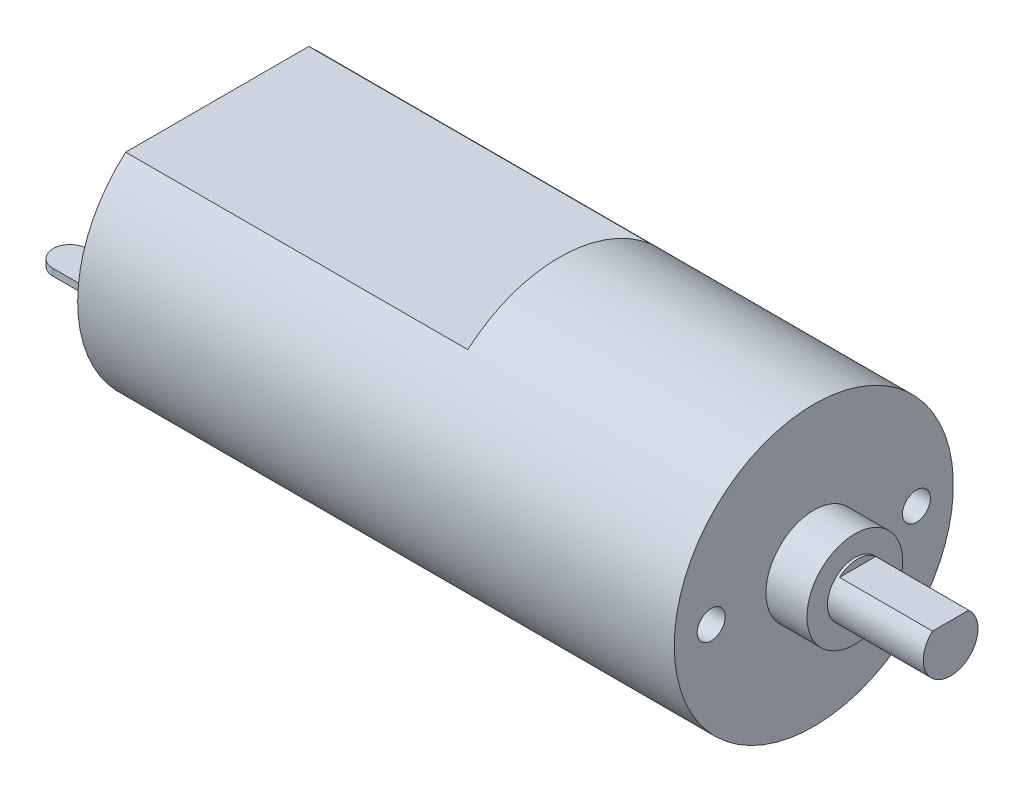
SolidWorks part; units mm, degrees
ref_plane "Front Plane" through (0, 0, 0) normal (0, 0, 1) x (1, 0, 0)
ref_plane "Top Plane" through (0, 0, 0) normal (0, 1, 0) x (1, 0, 0)
ref_plane "Right Plane" through (0, 0, 0) normal (1, 0, 0) x (0, 0, -1)
sketch "Sketch1" plane through (0, 0, 0) normal (0, 0, 1) x (1, 0, 0)
  line L0 (-26.8, 0) -> (26.8, 0)
  line L1 (26.8, 0) -> (26.8, 2)
  line L2 (26.8, 2) -> (19.8, 2)
  line L3 (19.8, 2) -> (19.8, 3.5)
  line L4 (19.8, 3.5) -> (16.8, 3.5)
  line L5 (16.8, 3.5) -> (16.8, 10.2)
  line L6 (16.8, 10.2) -> (-26.8, 10.2)
  line L7 (-26.8, 10.2) -> (-26.8, 0)
  point P4 (0, 0)
  dimension "D1" = 53.6
  dimension "D2" = 7
  dimension "D3" = 3
  dimension "D4" = 2
  dimension "D5" = 3.5
  dimension "D6" = 10.2
revolve "Revolve1" add sketch "Sketch1" angle 360 about L0
sketch "Sketch3" plane through (26.8, 0, 0) normal (1, 0, 0) x (0, 0, -1)
  line L0 (-1.3229, 1.5) -> (1.3229, 1.5)
  circle A0 centre (0, 0) radius 2 construction
  circle A2 centre (0, 0) radius 2 construction
  arc A3 (1.3229, 1.5) -> (-1.3229, 1.5) centre (0, 0) ccw
  point P0 (0, 0)
  point P5 (0, 1.5)
  dimension "D1" = 3.5
extrude "Cut-Extrude1" cut sketch "Sketch3" against normal blind 6.8
sketch "Sketch4" plane through (-26.8, 0, 0) normal (-1, 0, 0) x (0, 0, 1)
  line L0 (-6.6895, 7.7) -> (6.6895, 7.7)
  line L1 (-6.6895, -7.7) -> (6.6895, -7.7)
  line L2 (0, 0) -> (10.2, 0) construction
  circle A0 centre (0, 0) radius 10.2 construction
  arc A1 (6.6895, 7.7) -> (-6.6895, 7.7) centre (0, 0) ccw
  arc A2 (-6.6895, -7.7) -> (6.6895, -7.7) centre (0, 0) ccw
  point P5 (0, 7.7)
  point P8 (0, -7.7)
  dimension "D1" = 15.4
extrude "Cut-Extrude2" cut sketch "Sketch4" against normal blind 25
hole_wizard "M2.5x0.45 Tapped Hole1" positions "Sketch5" profile "Sketch6" tap size "M2.5x0.45" standard "ANSI Metric"
sketch "Sketch5" plane through (16.8, 0, 0) normal (1, 0, 0) x (0, 0, -1)
  circle A0 centre (0, 0) radius 7.5 construction
  point P0 (-7.5, 0)
  point P2 (7.5, 0)
  point P8 (0, 0)
  point P9 (0, 0)
  dimension "D1" = 15
sketch "Sketch6" plane through (16.8, 0, 7.5) normal (0, 1, 0) x (0, 0, -1)
  line L0 (0, 0) -> (0, 6.9659)
  line L1 (0, 6.9659) -> (1.025, 6.35)
  line L2 (1.025, 6.35) -> (1.025, 0)
  line L5 (1.025, 0) -> (0, 0)
  line L10 (0, 6.9659) -> (-1.025, 6.35) construction
  line L11 (0, -6.35) -> (0, 107.95) construction
  dimension "Tap Drill Dia." = 2.05
  dimension "Tap Drill Depth" = 6.35
  dimension "Drill Angle" = 118
cosmetic thread "Hole Thread1" parameters "D1"=5, "D2"=2.5
cosmetic thread "Hole Thread2" parameters "D1"=5, "D2"=2.5
sketch "Sketch7" plane through (0, 0, 0) normal (0, 1, 0) x (1, 0, 0)
  line L0 (-26.8, 9.25) -> (-29.55, 9.25)
  line L1 (-26.8, 10.2) -> (-26.8, 6.6895) construction
  line L2 (-29.55, 6.75) -> (-26.8, 6.75)
  line L3 (-26.8, 6.75) -> (-26.8, 9.25)
  line L4 (0, 0) -> (-26.8, 0) construction
  line L5 (-26.8, 6.6895) -> (-26.8, -6.6895) construction
  line L6 (-26.8, -6.75) -> (-26.8, -9.25)
  line L7 (-29.55, -6.75) -> (-26.8, -6.75)
  line L8 (-26.8, -9.25) -> (-29.55, -9.25)
  arc A0 (-29.55, 9.25) -> (-29.55, 6.75) centre (-29.55, 8) ccw
  arc A1 (-29.55, -9.25) -> (-29.55, -6.75) centre (-29.55, -8) cw
  point P6 (-28.175, 9.25)
  point P8 (-26.8, 8)
  dimension "D1" = 2.5
  dimension "D2" = 4
  dimension "D3" = 8
extrude "Boss-Extrude1" add sketch "Sketch7" along normal mid plane 0.5
sketch "Sketch8" plane through (-26.8, 0, 0) normal (-1, 0, 0) x (0, 0, 1)
  circle A0 centre (0, 0) radius 3
  dimension "D1" = 6
extrude "Boss-Extrude2" add sketch "Sketch8" along normal blind 2
